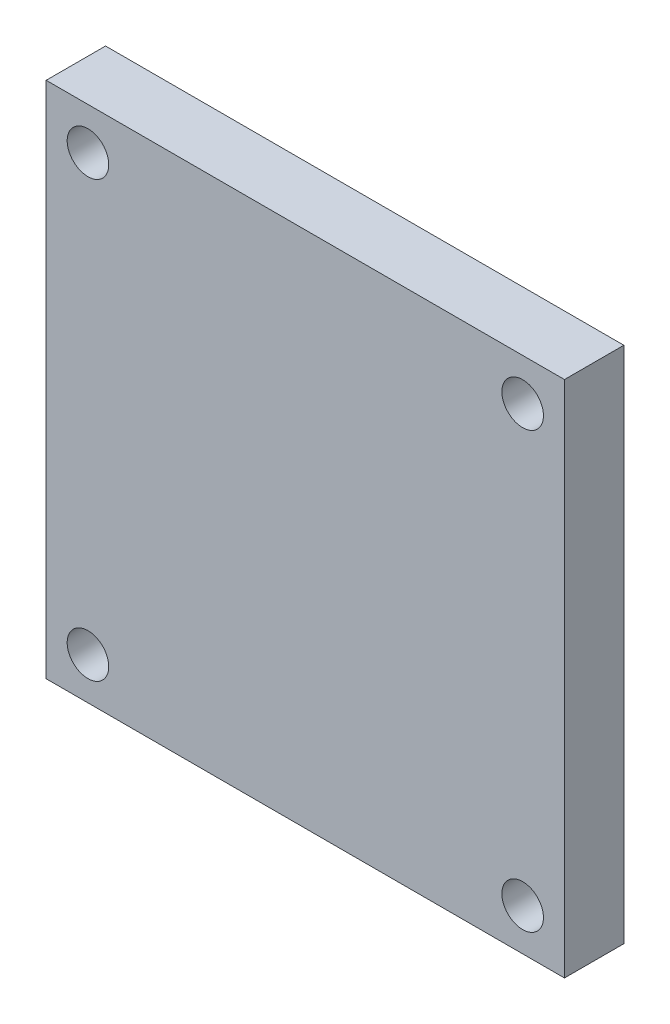
SolidWorks part; units mm, degrees
ref_plane "前视基准面" through (0, 0, 0) normal (0, 0, 1) x (1, 0, 0)
ref_plane "上视基准面" through (0, 0, 0) normal (0, 1, 0) x (1, 0, 0)
ref_plane "右视基准面" through (0, 0, 0) normal (1, 0, 0) x (0, 0, -1)
sketch "草图1" plane through (0, 0, 0) normal (0, 0, 1) x (1, 0, 0)
  line L0 (-18.3, 18.3) -> (18.3, 18.3) construction
  line L1 (-21.82, 21.82) -> (21.82, 21.82)
  line L2 (-21.82, 21.82) -> (-21.82, -21.82)
  line L3 (-21.82, -21.82) -> (21.82, -21.82)
  line L4 (21.82, 21.82) -> (21.82, -21.82)
  line L5 (-21.82, 21.82) -> (21.82, -21.82) construction
  line L6 (-21.82, -21.82) -> (21.82, 21.82) construction
  circle A0 centre (-18.3, -18.3) radius 1.75
  circle A1 centre (-18.3, 18.3) radius 1.75
  circle A2 centre (18.3, 18.3) radius 1.75
  circle A3 centre (18.3, -18.3) radius 1.75
  point P0 (0, 0)
  point P7 (0, 0)
  point P9 (-18.3, -18.3)
  point P10 (0, 0)
  point P11 (0, 0)
  point P19 (0, 0)
  dimension "D1" = 4
  dimension "D2" = 43.64
  dimension "D3" = 36.6
extrude "凸台-拉伸1" add sketch "草图1" along normal blind 5
